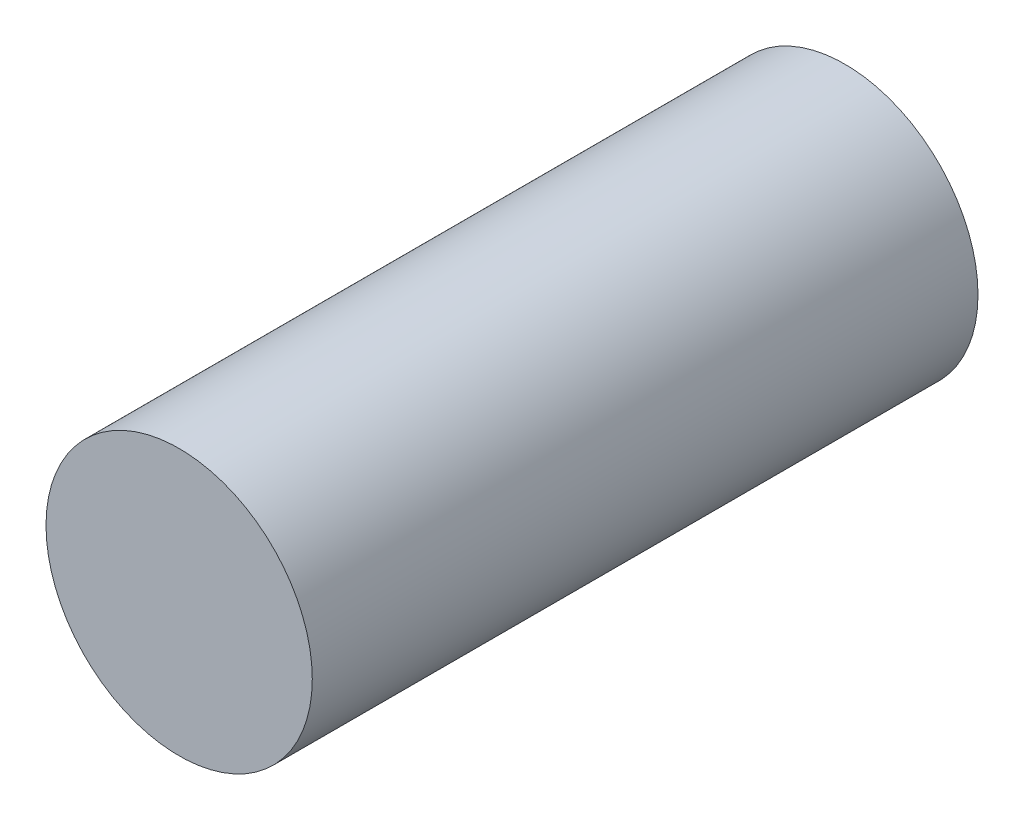
SolidWorks part; units mm, degrees
ref_plane "Front Plane" through (0, 0, 0) normal (0, 0, 1) x (1, 0, 0)
ref_plane "Top Plane" through (0, 0, 0) normal (0, 1, 0) x (1, 0, 0)
ref_plane "Right Plane" through (0, 0, 0) normal (1, 0, 0) x (0, 0, -1)
other "Configuration Table"
sketch "Sketch1" plane through (0, 0, 0) normal (0, 0, 1) x (1, 0, 0)
  circle A0 centre (300, 924) radius 4
extrude "TOPPING_kat3_kapak_pimi_D8_1" add sketch "Sketch1" against normal blind 20 from offset 40 separate body
